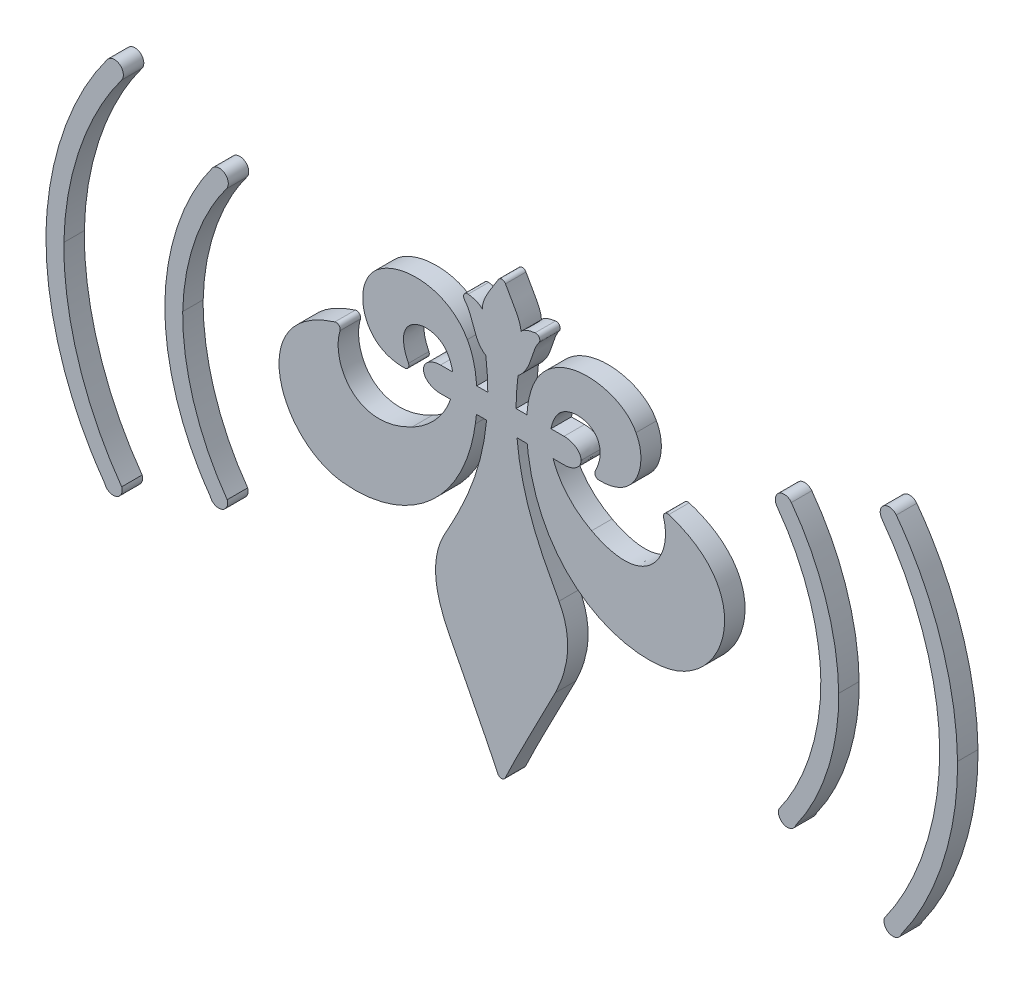
SolidWorks part; units mm, degrees
ref_plane "Front Plane" through (0, 0, 0) normal (0, 0, 1) x (1, 0, 0)
ref_plane "Top Plane" through (0, 0, 0) normal (0, 1, 0) x (1, 0, 0)
ref_plane "Right Plane" through (0, 0, 0) normal (1, 0, 0) x (0, 0, -1)
sketch "Model" plane through (0, 0, 0) normal (0, 0, 1) x (1, 0, 0)
  line L0 (-91.0142, 254.4051) -> (-92.3852, 254.4051)
  line L1 (-95.3712, 254.4051) -> (-96.8828, 254.4051)
  line L2 (-96.8828, 251.3309) -> (-95.641, 251.3309)
  line L3 (-92.4284, 251.3309) -> (-91.1584, 251.3309)
  line L4 (-87.3892, 251.3309) -> (-86.1192, 251.3309)
  line L5 (-82.907, 251.3309) -> (-81.5488, 251.3309)
  line L6 (-81.5488, 254.4051) -> (-83.1766, 254.4051)
  line L7 (-86.1627, 254.4051) -> (-87.51, 254.4051)
  arc A0 (-53.3252, 261.3934) -> (-55.1038, 260.0716) centre (-54.2145, 260.7325) ccw
  arc A1 (-54.8787, 227.6601) -> (-52.7658, 226.9919) centre (-53.8223, 227.326) ccw
  arc A2 (-40.2952, 266.5598) -> (-42.0738, 265.238) centre (-41.1845, 265.8989) ccw
  arc A3 (-41.7763, 222.4942) -> (-39.6635, 221.826) centre (-40.7199, 222.1601) ccw
  arc A4 (-136.4853, 265.238) -> (-138.264, 266.5598) centre (-137.3746, 265.8989) ccw
  arc A5 (-138.5846, 220.8425) -> (-136.4718, 221.5108) centre (-137.5282, 221.1766) ccw
  arc A6 (-123.4553, 260.0716) -> (-125.234, 261.3934) centre (-124.3446, 260.7325) ccw
  arc A7 (-125.4824, 226.0089) -> (-123.3695, 226.6771) centre (-124.426, 226.343) ccw
  spline S0 degree 3 poles (-52.7658, 226.9919) (-49.3239, 231.7614) (-47.3715, 237.9346) (-47.4449, 243.816) knots 0 0 0 0 1 1 1 1
  spline S1 degree 3 poles (-47.4449, 243.816) (-47.522, 249.9938) (-49.64, 256.4345) (-53.3252, 261.3934) knots 0 0 0 0 1.00991 1.00991 1.00991 1.00991
  spline S2 degree 3 poles (-55.1038, 260.0716) (-51.7573, 255.5684) (-49.7728, 249.7523) (-49.6658, 244.1428) knots 0 0 0 0 0.989781 0.989781 0.989781 0.989781
  spline S3 degree 3 poles (-49.6658, 244.1428) (-49.5938, 238.3808) (-51.5066, 232.3329) (-54.8787, 227.6601) knots 0 0 0 0 1 1 1 1
  spline S4 degree 3 poles (-39.6635, 221.826) (-35.1524, 228.077) (-32.5936, 236.1676) (-32.6898, 243.8758) knots 0 0 0 0 1 1 1 1
  spline S5 degree 3 poles (-32.6898, 243.8758) (-32.7894, 251.8502) (-35.5383, 260.1588) (-40.2952, 266.5598) knots 0 0 0 0 1.007595 1.007595 1.007595 1.007595
  spline S6 degree 3 poles (-42.0738, 265.238) (-37.6557, 259.2928) (-35.0402, 251.609) (-34.9105, 244.203) knots 0 0 0 0 0.992225 0.992225 0.992225 0.992225
  spline S7 degree 3 poles (-34.9105, 244.203) (-34.8158, 236.6141) (-37.335, 228.6485) (-41.7763, 222.4942) knots 0 0 0 0 1 1 1 1
  spline S8 degree 3 poles (-87.51, 254.4051) (-87.4975, 255.5745) (-87.4217, 256.7951) (-87.2653, 258.072) knots 0 0 0 0 1 1 1 1
  spline S9 degree 3 poles (-87.2653, 258.072) (-85.0539, 259.8873) (-85.9452, 262.4287) (-83.6838, 263.816) knots 0 0 0 0 1 1 1 1
  spline S10 degree 3 poles (-83.6838, 263.816) (-85.2333, 263.8568) (-86.4972, 263.553) (-86.9049, 262.9822) knots 0 0 0 0 1 1 1 1
  spline S11 degree 3 poles (-86.9049, 262.9822) (-86.9049, 264.3316) (-88.3498, 266.0215) (-89.2465, 268.0414) knots 0 0 0 0 1 1 1 1
  spline S12 degree 3 poles (-89.2465, 268.0414) (-90.2117, 266.0327) (-91.6925, 264.6374) (-91.6925, 262.9822) knots 0 0 0 0 1 1 1 1
  spline S13 degree 3 poles (-91.6925, 262.9822) (-92.1003, 263.553) (-93.3643, 263.8568) (-94.9136, 263.816) knots 0 0 0 0 1 1 1 1
  spline S14 degree 3 poles (-94.9136, 263.816) (-92.4473, 262.1979) (-93.2063, 259.4913) (-91.2591, 258.237) knots 0 0 0 0 1 1 1 1
  spline S15 degree 3 poles (-91.2591, 258.237) (-91.0959, 256.9032) (-91.0221, 255.6264) (-91.0142, 254.4051) knots 0 0 0 0 1 1 1 1
  spline S16 degree 3 poles (-92.3852, 254.4051) (-92.4986, 256.0206) (-92.8495, 257.5657) (-93.5485, 258.7993) knots 0 0 0 0 1 1 1 1
  spline S17 degree 3 poles (-93.5485, 258.7993) (-96.4633, 263.9429) (-104.1659, 262.8624) (-105.9293, 259.2579) knots 0 0 0 0 1 1 1 1
  spline S18 degree 3 poles (-105.9293, 259.2579) (-107.5338, 256.4306) (-106.0582, 251.1916) (-100.5052, 251.9225) knots 0 0 0 0 1 1 1 1
  spline S19 degree 3 poles (-100.5052, 251.9225) (-103.7908, 257.4239) (-97.904, 258.7993) (-96.1463, 256.2777) knots 0 0 0 0 1 1 1 1
  spline S20 degree 3 poles (-96.1463, 256.2777) (-95.7494, 255.7083) (-95.4947, 255.0746) (-95.3712, 254.4051) knots 0 0 0 0 1 1 1 1
  spline S21 degree 3 poles (-96.8828, 254.4051) (-98.0542, 254.4051) (-99.0038, 253.717) (-99.0038, 252.868) knots 0 0 0 0 1 1 1 1
  spline S22 degree 3 poles (-99.0038, 252.868) (-99.0038, 252.019) (-98.0542, 251.3309) (-96.8828, 251.3309) knots 0 0 0 0 1 1 1 1
  spline S23 degree 3 poles (-95.641, 251.3309) (-96.3355, 249.2549) (-98.0146, 247.2301) (-100.4252, 245.9626) knots 0 0 0 0 1 1 1 1
  spline S24 degree 3 poles (-100.4252, 245.9626) (-107.8374, 242.0656) (-111.0464, 248.9425) (-108.9833, 252.763) knots 0 0 0 0 1 1 1 1
  spline S25 degree 3 poles (-108.9833, 252.763) (-121.6673, 249.6302) (-117.264, 236.6636) (-109.0598, 235.7237) knots 0 0 0 0 1 1 1 1
  spline S26 degree 3 poles (-109.0598, 235.7237) (-101.7245, 234.8831) (-94.0073, 240.0025) (-92.5553, 250.2414) knots 0 0 0 0 1 1 1 1
  spline S27 degree 3 poles (-92.5553, 250.2414) (-92.5047, 250.5983) (-92.4618, 250.9626) (-92.4284, 251.3309) knots 0 0 0 0 1 1 1 1
  spline S28 degree 3 poles (-91.1584, 251.3309) (-91.8291, 244.4179) (-94.7187, 239.5458) (-96.4282, 236.3628) knots 0 0 0 0 1 1 1 1
  spline S29 degree 3 poles (-96.4282, 236.3628) (-98.6593, 232.2086) (-96.8485, 228.1162) (-95.9666, 226.285) knots 0 0 0 0 1 1 1 1
  spline S30 degree 3 poles (-95.9666, 226.285) (-94.9664, 224.208) (-90.4692, 215.8124) (-89.3154, 212.9661) knots 0 0 0 0 1 1 1 1
  spline S31 degree 3 poles (-89.3154, 212.9661) (-88.1615, 215.8124) (-83.6304, 224.208) (-82.6302, 226.285) knots 0 0 0 0 1 1 1 1
  spline S32 degree 3 poles (-82.6302, 226.285) (-81.7486, 228.1162) (-79.9377, 232.2086) (-82.1688, 236.3628) knots 0 0 0 0 1 1 1 1
  spline S33 degree 3 poles (-82.1688, 236.3628) (-83.8899, 239.5677) (-86.7646, 244.3865) (-87.3892, 251.3309) knots 0 0 0 0 1 1 1 1
  spline S34 degree 3 poles (-86.1192, 251.3309) (-86.0854, 250.9628) (-86.0429, 250.5983) (-85.9922, 250.2414) knots 0 0 0 0 1 1 1 1
  spline S35 degree 3 poles (-85.9922, 250.2414) (-84.5404, 240.0027) (-76.8232, 234.8831) (-69.4879, 235.7237) knots 0 0 0 0 1 1 1 1
  spline S36 degree 3 poles (-69.4879, 235.7237) (-61.2836, 236.6638) (-56.8802, 249.6303) (-69.5646, 252.763) knots 0 0 0 0 1 1 1 1
  spline S37 degree 3 poles (-69.5646, 252.763) (-67.5016, 248.9425) (-70.7107, 242.0656) (-78.1228, 245.9626) knots 0 0 0 0 1 1 1 1
  spline S38 degree 3 poles (-78.1228, 245.9626) (-80.5334, 247.2301) (-82.2123, 249.2549) (-82.907, 251.3309) knots 0 0 0 0 1 1 1 1
  spline S39 degree 3 poles (-81.5488, 251.3309) (-80.3774, 251.3309) (-79.4277, 252.0189) (-79.4277, 252.868) knots 0 0 0 0 1 1 1 1
  spline S40 degree 3 poles (-79.4277, 252.868) (-79.4277, 253.7169) (-80.3774, 254.4051) (-81.5488, 254.4051) knots 0 0 0 0 1 1 1 1
  spline S41 degree 3 poles (-83.1766, 254.4051) (-83.053, 255.0746) (-82.7985, 255.7083) (-82.4017, 256.2777) knots 0 0 0 0 1 1 1 1
  spline S42 degree 3 poles (-82.4017, 256.2777) (-80.6439, 258.7993) (-74.757, 257.4239) (-78.0427, 251.9225) knots 0 0 0 0 1 1 1 1
  spline S43 degree 3 poles (-78.0427, 251.9225) (-72.4897, 251.1916) (-71.014, 256.4308) (-72.6186, 259.2579) knots 0 0 0 0 1 1 1 1
  spline S44 degree 3 poles (-72.6186, 259.2579) (-74.3821, 262.8624) (-82.0847, 263.9427) (-84.9995, 258.7993) knots 0 0 0 0 1 1 1 1
  spline S45 degree 3 poles (-84.9995, 258.7993) (-85.6984, 257.5657) (-86.0494, 256.0206) (-86.1627, 254.4051) knots 0 0 0 0 1 1 1 1
  spline S46 degree 3 poles (-136.4718, 221.5108) (-141.1143, 227.9439) (-143.7476, 236.2703) (-143.6486, 244.203) knots 0 0 0 0 1 1 1 1
  spline S47 degree 3 poles (-143.6486, 244.203) (-143.5189, 251.609) (-140.9034, 259.2928) (-136.4853, 265.238) knots 0 0 0 0 0.992225 0.992225 0.992225 0.992225
  spline S48 degree 3 poles (-138.264, 266.5598) (-143.0208, 260.1588) (-145.7697, 251.8502) (-145.8693, 243.8758) knots 0 0 0 0 1.007595 1.007595 1.007595 1.007595
  spline S49 degree 3 poles (-145.8693, 243.8758) (-145.9699, 235.8238) (-143.2969, 227.3724) (-138.5846, 220.8425) knots 0 0 0 0 1 1 1 1
  spline S50 degree 3 poles (-123.3695, 226.6771) (-126.9428, 231.6285) (-128.9696, 238.0371) (-128.8933, 244.1428) knots 0 0 0 0 1 1 1 1
  spline S51 degree 3 poles (-128.8933, 244.1428) (-128.7863, 249.7523) (-126.8018, 255.5685) (-123.4553, 260.0716) knots 0 0 0 0 0.989781 0.989781 0.989781 0.989781
  spline S52 degree 3 poles (-125.234, 261.3934) (-128.9192, 256.4345) (-131.0371, 249.9938) (-131.1142, 243.816) knots 0 0 0 0 1.00991 1.00991 1.00991 1.00991
  spline S53 degree 3 poles (-131.1142, 243.816) (-131.1919, 237.591) (-129.1255, 231.0571) (-125.4824, 226.0089) knots 0 0 0 0 1 1 1 1
extrude "Boss-Extrude1" add sketch "Model" along normal blind 2.54
fillet "Fillet2" radius 0.508 1 edges at (-89.3154, 212.9661, 1.27)
fillet "Fillet3" radius 0.508 1 edges at (-89.2465, 268.0414, 1.27)
fillet "Fillet4" radius 0.508 1 edges at (-94.9136, 263.816, 1.27)
fillet "Fillet5" radius 0.508 1 edges at (-83.6838, 263.816, 1.27)
fillet "Fillet6" radius 0.508 1 edges at (-78.0427, 251.9225, 1.27)
fillet "Fillet7" radius 0.508 1 edges at (-100.5052, 251.9225, 1.27)
fillet "Fillet8" radius 0.508 1 edges at (-69.5646, 252.763, 1.27)
fillet "Fillet9" radius 0.508 1 edges at (-108.9833, 252.763, 1.27)
